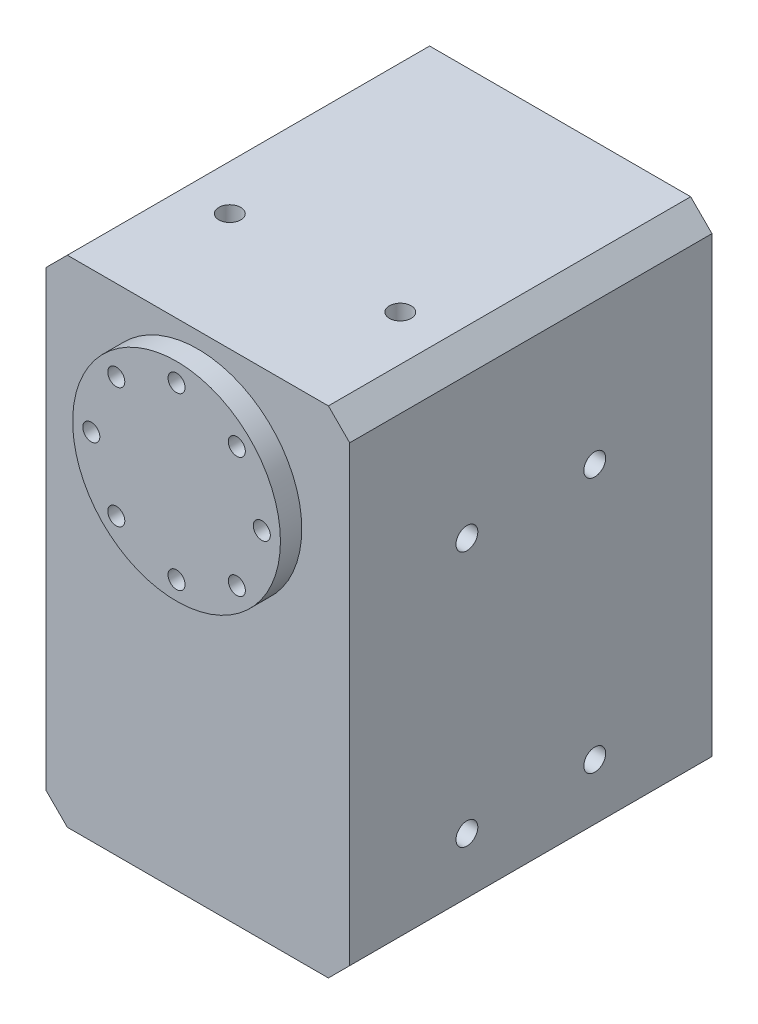
SolidWorks part; units mm, degrees
ref_plane "Plan de face" through (0, 0, 0) normal (0, 0, 1) x (1, 0, 0)
ref_plane "Plan de dessus" through (0, 0, 0) normal (0, 1, 0) x (1, 0, 0)
ref_plane "Plan de droite" through (0, 0, 0) normal (1, 0, 0) x (0, 0, -1)
sketch "Esquisse1" plane through (0, 0, 0) normal (0, 0, 1) x (1, 0, 0)
  line L1 (-14.25, 23.25) -> (14.25, 23.25)
  line L2 (-14.25, 23.25) -> (-14.25, -23.25)
  line L3 (-14.25, -23.25) -> (14.25, -23.25)
  line L4 (14.25, 23.25) -> (14.25, -23.25)
  point P4 (0, 23.25)
  point P6 (14.25, 0)
  dimension "D1" = 28.5
  dimension "D2" = 46.5
extrude "Boss.-Extru.1" add sketch "Esquisse1" along normal blind 34
sketch "Esquisse2" plane through (0, 0, 34) normal (0, 0, 1) x (1, 0, 0)
  line L0 (14.25, 23.25) -> (-14.25, 23.25) construction
  circle A0 centre (0, 12) radius 9.75
  circle A1 centre (0, 20) radius 0.8
  circle A2 centre (5.6569, 17.6569) radius 0.8
  circle A3 centre (8, 12) radius 0.8
  circle A4 centre (5.6569, 6.3431) radius 0.8
  circle A5 centre (0, 4) radius 0.8
  circle A6 centre (-5.6569, 6.3431) radius 0.8
  circle A7 centre (-8, 12) radius 0.8
  circle A8 centre (-5.6569, 17.6569) radius 0.8
  point P2 (0, 12)
  point P3 (0, 4)
  point P6 (0, 23.25)
  point P24 (0, 12)
  dimension "D2" = 19.5
  dimension "D3" = 1.6
  dimension "D1" = 11.25
  dimension "D4" = 8
  dimension "D5" = 8
extrude "Boss.-Extru.2" add sketch "Esquisse2" along normal blind 2
sketch "Esquisse3" plane through (0, 23.25, 0) normal (0, 1, 0) x (1, 0, 0)
  line L0 (14.25, -34) -> (-14.25, -34) construction
  line L1 (-14.25, -34) -> (-14.25, 0) construction
  circle A0 centre (-8, -23) radius 1.025
  circle A1 centre (8, -23) radius 1.025
  point P6 (0, 0)
  dimension "D4" = 2.05
  dimension "D1" = 11
  dimension "D2" = 6.25
  dimension "D3" = 16
extrude "Enlèv. mat.-Extru.1" cut sketch "Esquisse3" against normal blind 3
sketch "Esquisse4" plane through (-14.25, 0, 0) normal (-1, 0, 0) x (0, 0, 1)
  line L0 (34, -23.25) -> (0, -23.25) construction
  line L1 (34, 23.25) -> (34, -23.25) construction
  circle A0 centre (23, 8) radius 1.025
  circle A1 centre (11, 8) radius 1.025
  circle A2 centre (23, -16) radius 1.025
  circle A3 centre (11, -16) radius 1.025
  point P8 (7.9071, 5.7657)
  point P9 (0, 0)
  point P10 (0, 0)
  point P11 (0, 0)
  point P12 (0, 0)
  point P13 (0, 0)
  dimension "D4" = 2.05
  dimension "D1" = 7.25
  dimension "D2" = 24
  dimension "D3" = 12
  dimension "D5" = 11
extrude "Enlèv. mat.-Extru.2" cut sketch "Esquisse4" against normal blind 3
sketch "Esquisse5" plane through (14.25, 0, 0) normal (1, 0, 0) x (0, 0, -1)
  circle A0 centre (-11, -16) radius 1.025 construction
  circle A1 centre (-23, -16) radius 1.025 construction
  circle A2 centre (-23, 8) radius 1.025 construction
  circle A3 centre (-11, 8) radius 1.025 construction
  circle A4 centre (-11, -16) radius 1.025
  circle A5 centre (-23, -16) radius 1.025
  circle A6 centre (-23, 8) radius 1.025
  circle A7 centre (-11, 8) radius 1.025
extrude "Enlèv. mat.-Extru.3" cut sketch "Esquisse5" against normal blind 3
sketch "Esquisse6" plane through (0, -23.25, 0) normal (0, -1, 0) x (1, 0, 0)
  circle A0 centre (-8, 23) radius 1.025 construction
  circle A1 centre (8, 23) radius 1.025 construction
  circle A2 centre (-8, 23) radius 1.025
  circle A3 centre (8, 23) radius 1.025
  circle A4 centre (-8, 11) radius 1.025
  circle A5 centre (8, 11) radius 1.025
  point P10 (0, 0)
  point P11 (0, 0)
  point P12 (0, 0)
  dimension "D1" = 12
extrude "Enlèv. mat.-Extru.4" cut sketch "Esquisse6" against normal blind 3
chamfer "Chanfrein1" distance 2 angle 45 4 edges at (14.25, -23.25, 17) (14.25, 23.25, 17) (-14.25, 23.25, 17) (-14.25, -23.25, 17)
